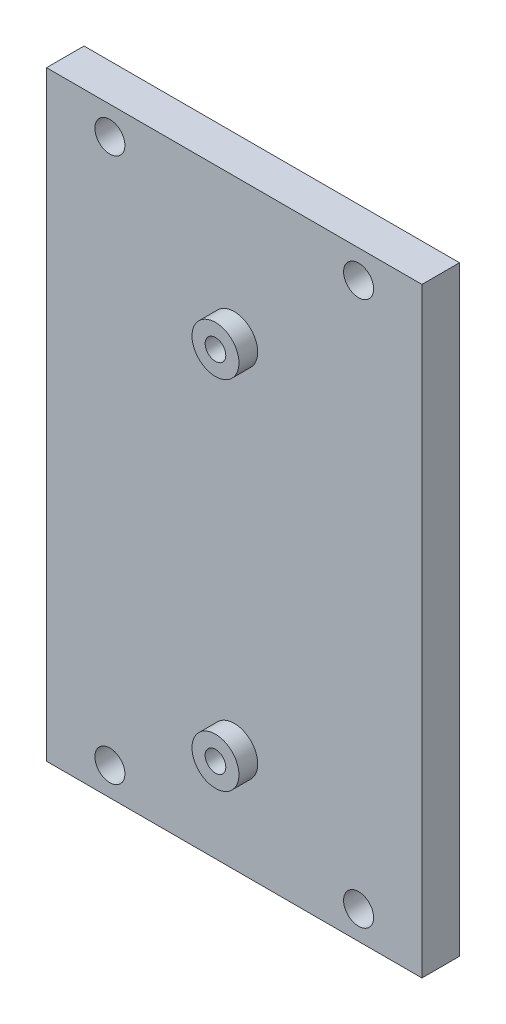
SolidWorks part; units mm, degrees
ref_plane "Front Plane" through (0, 0, 0) normal (0, 0, 1) x (1, 0, 0)
ref_plane "Top Plane" through (0, 0, 0) normal (0, 1, 0) x (1, 0, 0)
ref_plane "Right Plane" through (0, 0, 0) normal (1, 0, 0) x (0, 0, -1)
sketch "Эскиз1" plane through (0, 0, 0) normal (0, 0, 1) x (1, 0, 0)
  line L0 (-35.9307, 28) -> (39.4026, 28) construction
  line L1 (-20, -32) -> (20, -32)
  line L2 (-20, -32) -> (-20, 32)
  line L3 (-20, 32) -> (20, 32)
  line L4 (20, -32) -> (20, 32)
  line L5 (-20, -32) -> (20, 32) construction
  line L6 (-20, 32) -> (20, -32) construction
  line L7 (-20, 28) -> (20, -32) construction
  line L8 (-20, -32) -> (20, 28) construction
  line L9 (0, -2) -> (20, -2) construction
  line L10 (-13.25, 29) -> (13.25, 29) construction
  line L11 (-13.25, 29) -> (-13.25, -29) construction
  line L12 (-13.25, -29) -> (13.25, -29) construction
  line L13 (13.25, 29) -> (13.25, -29) construction
  line L14 (-13.25, 29) -> (13.25, -29) construction
  line L15 (-13.25, -29) -> (13.25, 29) construction
  line L16 (0, -2) -> (-20, -2) construction
  line L17 (-25.9271, -21) -> (26.391, -21) construction
  line L18 (-25.9271, 17) -> (26.391, 17) construction
  line L19 (0, 32) -> (0, -32) construction
  circle A0 centre (-13.25, 29) radius 1.6
  circle A1 centre (13.25, 29) radius 1.6
  circle A2 centre (-13.25, -29) radius 1.6
  circle A3 centre (13.25, -29) radius 1.6
  circle A4 centre (0, -21) radius 1.1
  circle A5 centre (0, 17) radius 1.1
  point P0 (0, 0)
  point P9 (0, 0)
  dimension "D6" = 3.2
  dimension "D7" = 19
  dimension "D9" = 2.2
  dimension "D1" = 40
  dimension "D2" = 64
  dimension "D3" = 4
  dimension "D4" = 26.5
  dimension "D5" = 58
  dimension "D8" = 19
extrude "Бобышка-Вытянуть1" add sketch "Эскиз1" along normal blind 4
sketch "Эскиз2" plane through (0, 0, 4) normal (0, 0, 1) x (1, 0, 0)
  circle A0 centre (0, 17) radius 2.5
  circle A1 centre (0, -21) radius 2.5
  circle A2 centre (0, -21) radius 1.1
  circle A3 centre (0, 17) radius 1.1
  dimension "D1" = 2.2
  dimension "D2" = 5
extrude "Бобышка-Вытянуть2" add sketch "Эскиз2" along normal blind 2
